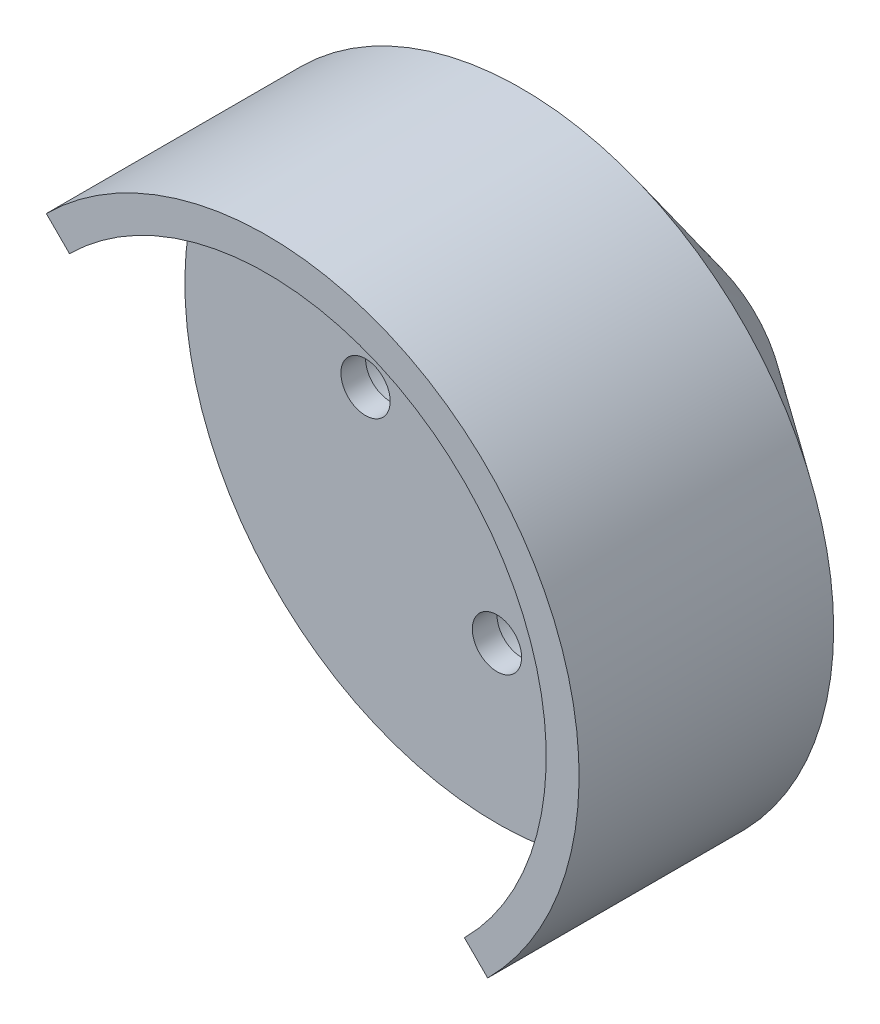
SolidWorks part; units mm, degrees
ref_plane "Alzado" through (0, 0, 0) normal (0, 0, 1) x (1, 0, 0)
ref_plane "Planta" through (0, 0, 0) normal (0, 1, 0) x (1, 0, 0)
ref_plane "Vista lateral" through (0, 0, 0) normal (1, 0, 0) x (0, 0, -1)
sketch "Croquis1" plane through (0, 0, 0) normal (0, 0, 1) x (1, 0, 0)
  line L0 (-84.957, 9.6398) -> (-76.957, 9.6398) construction
  line L1 (-84.957, 9.6398) -> (-92.957, 9.6398) construction
  line L2 (-84.957, 9.6398) -> (-84.957, 19.1398) construction
  line L3 (-84.957, 9.6398) -> (-84.957, 0.1398) construction
  line L4 (-84.957, 9.6398) -> (-71.522, 23.0748) construction
  line L5 (-84.957, 9.6398) -> (-98.392, 23.0748) construction
  line L6 (-98.392, 23.0748) -> (-71.522, -3.7952) construction
  circle A0 centre (-84.957, 9.6398) radius 19
  circle A1 centre (-84.957, 19.1398) radius 1.5
  circle A2 centre (-92.957, 9.6398) radius 1.5
  circle A3 centre (-84.957, 0.1398) radius 1.5
  circle A4 centre (-76.957, 9.6398) radius 1.5
  dimension "D1" = 38
  dimension "D2" = 8
  dimension "D3" = 8
  dimension "D4" = 9.5
  dimension "D5" = 9.5
extrude "Saliente-Extruir1" add sketch "Croquis1" along normal blind 1.5
sketch "Croquis2" plane through (0, 0, 1.5) normal (0, 0, 1) x (1, 0, 0)
  line L0 (-84.957, 9.6398) -> (-71.522, -3.7952) construction
  line L1 (-71.522, -3.7952) -> (-98.392, 23.0748) construction
  line L2 (-98.392, 23.0748) -> (-96.9778, 21.6606)
  line L3 (-71.522, -3.7952) -> (-72.9362, -2.381)
  circle A0 centre (-84.957, 9.6398) radius 19 construction
  arc A1 (-98.392, 23.0748) -> (-71.522, -3.7952) centre (-84.957, 9.6398) cw
  arc A2 (-96.9778, 21.6606) -> (-72.9362, -2.381) centre (-84.957, 9.6398) cw
extrude "Saliente-Extruir2" add sketch "Croquis2" along normal blind 14
sketch "Croquis3" plane through (0, 0, 0) normal (0, 0, -1) x (-1, 0, 0)
  circle A0 centre (84.957, 9.6398) radius 19
  circle A1 centre (84.957, 0.1398) radius 3
  circle A2 centre (76.957, 9.6398) radius 3
  circle A3 centre (92.957, 9.6398) radius 3
  circle A4 centre (84.957, 19.1398) radius 3
extrude "Saliente-Extruir3" add sketch "Croquis3" along normal blind 10
sketch "Croquis4" plane through (0, 0, -10) normal (0, 0, -1) x (-1, 0, 0)
  line L0 (84.957, 9.6398) -> (103.957, 9.6398)
  circle A0 centre (84.957, 9.6398) radius 19 construction
ref_plane "Plano1" through (0, 9.6398, 0) normal (0, -1, 0) x (-1, 0, 0)
sketch "Croquis5" plane through (0, 9.6398, 0) normal (0, -1, 0) x (-1, 0, 0)
  line L0 (103.957, 10) -> (103.957, 0) construction
  line L1 (103.957, -1.5) -> (103.957, 10) construction
  line L2 (103.957, 0) -> (84.957, 0) construction
  line L4 (84.957, 0) -> (84.957, 10) construction
  line L6 (84.957, 10) -> (90.957, 10) construction
  line L7 (84.957, 10) -> (103.957, 10) construction
  line L8 (90.957, 10) -> (103.957, 0)
  line L9 (103.957, 0) -> (103.957, 10)
  line L10 (103.957, 10) -> (90.957, 10)
revolve "Cortar-Revolución1" cut sketch "Croquis5" angle 360 about L4
